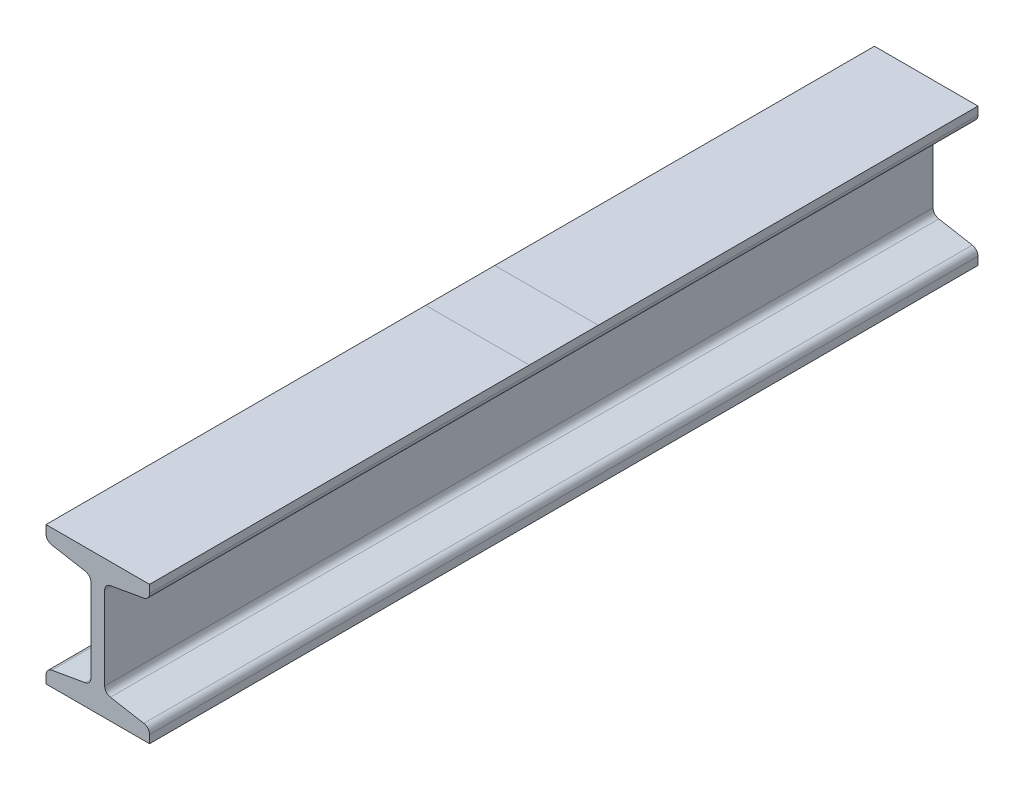
SolidWorks part; units mm, degrees
ref_plane "Front Plane" through (0, 0, 0) normal (0, 0, 1) x (1, 0, 0)
ref_plane "Top Plane" through (0, 0, 0) normal (0, 1, 0) x (1, 0, 0)
ref_plane "Right Plane" through (0, 0, 0) normal (1, 0, 0) x (0, 0, -1)
sketch "Sketch1" plane through (0, 0, 0) normal (0, 0, 1) x (1, 0, 0)
  line L0 (37.5, 50) -> (37.5, 40)
  line L1 (37.5, 40) -> (5, 34.2694)
  line L2 (5, 34.2694) -> (5, -34.2694)
  line L3 (5, -34.2694) -> (37.5, -40)
  line L4 (37.5, -40) -> (37.5, -50)
  line L5 (0, 24.2859) -> (0, 0) construction
  line L6 (0, 0) -> (-6.3859, 0) construction
  line L7 (-37.5, -40) -> (-37.5, -50)
  line L8 (-5, -34.2694) -> (-37.5, -40)
  line L9 (-5, 34.2694) -> (-5, -34.2694)
  line L10 (-37.5, 40) -> (-5, 34.2694)
  line L11 (-37.5, 50) -> (-37.5, 40)
  line L12 (-37.5, 50) -> (37.5, 50)
  line L13 (37.5, -50) -> (-37.5, -50)
  dimension "D1" = 100
  dimension "D2" = 75
  dimension "D3" = 10
  dimension "D4" = 100
  dimension "D5" = 10
extrude "Boss-Extrude1" add sketch "Sketch1" along normal blind 600
sketch "Sketch2" plane through (0, 50, 0) normal (0, 1, 0) x (1, 0, 0)
  line L0 (37.5, -600) -> (37.5, 0) construction
  line L1 (-37.5, -275) -> (37.5, -275)
  line L2 (-37.5, -275) -> (-37.5, -325)
  line L3 (-37.5, -325) -> (37.5, -325)
  line L4 (37.5, -275) -> (37.5, -325)
  line L5 (-37.5, -275) -> (37.5, -325) construction
  line L6 (-37.5, -325) -> (37.5, -275) construction
  point P0 (0, -300)
  dimension "D1" = 50
  dimension "D2" = 300
  dimension "D3" = 75
split line "Split Line1"
sketch "Sketch3" plane through (0, -50, 0) normal (0, -1, 0) x (1, 0, 0)
  line L0 (37.5, 600) -> (37.5, 0) construction
  line L1 (-37.5, 600) -> (37.5, 600)
  line L2 (-37.5, 600) -> (-37.5, 560)
  line L3 (-37.5, 560) -> (37.5, 560)
  line L4 (37.5, 600) -> (37.5, 560)
  line L5 (-37.5, 600) -> (-37.5, 0) construction
  line L6 (37.5, 0) -> (-37.5, 0)
  line L7 (37.5, 0) -> (37.5, 40)
  line L8 (37.5, 40) -> (-37.5, 40)
  line L9 (-37.5, 0) -> (-37.5, 40)
  dimension "D1" = 40
  dimension "D2" = 40
split line "Split Line2"
fillet "Fillet1" radius 5 8 edges at (-37.5, -40, 300) (-5, -34.2694, 300) (37.5, -40, 300) (5, -34.2694, 300) (5, 34.2694, 300) (-5, 34.2694, 300) (-37.5, 40, 300) (37.5, 40, 300)
